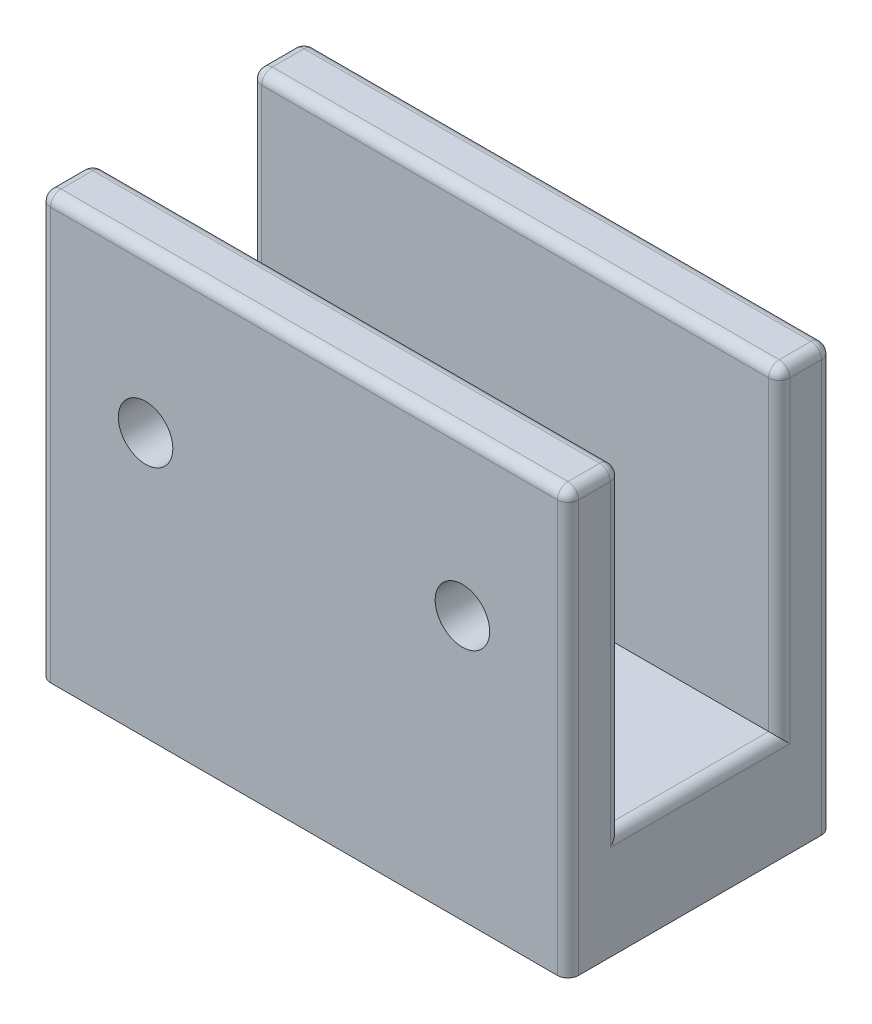
SolidWorks part; units mm, degrees
ref_plane "Front Plane" through (0, 0, 0) normal (0, 0, 1) x (1, 0, 0)
ref_plane "Top Plane" through (0, 0, 0) normal (0, 1, 0) x (1, 0, 0)
ref_plane "Right Plane" through (0, 0, 0) normal (1, 0, 0) x (0, 0, -1)
sketch "Sketch1" plane through (0, 0, 0) normal (0, 1, 0) x (1, 0, 0)
  line L1 (-25, -12.5) -> (25, -12.5)
  line L2 (-25, -12.5) -> (-25, 12.5)
  line L3 (-25, 12.5) -> (25, 12.5)
  line L4 (25, -12.5) -> (25, 12.5)
  line L5 (-25, -12.5) -> (25, 12.5) construction
  line L6 (-25, 12.5) -> (25, -12.5) construction
  point P0 (0, 0)
extrude "Boss-Extrude1" add sketch "Sketch1" along normal blind 40
sketch "Sketch2" plane through (0, 40, 0) normal (0, 1, 0) x (1, 0, 0)
  line L0 (25, -12.5) -> (25, 12.5) construction
  line L1 (-25, -7.5) -> (25, -7.5)
  line L2 (-25, -7.5) -> (-25, 7.5)
  line L3 (-25, 7.5) -> (25, 7.5)
  line L4 (25, -7.5) -> (25, 7.5)
  line L5 (-25, -7.5) -> (25, 7.5) construction
  line L6 (-25, 7.5) -> (25, -7.5) construction
  point P0 (0, 0)
extrude "Cut-Extrude1" cut sketch "Sketch2" against normal blind 30
fillet "Fillet1" radius 1 18 edges at (-25, 10, 0) (-25, 40, 10) (-25, 20, -12.5) (-25, 40, -10) (-25, 25, -7.5) (-25, 25, 7.5) (-25, 20, 12.5) (0, 40, 12.5) (0, 40, 7.5) (25, 40, -10) (25, 40, 10) (25, 20, 12.5) (25, 10, 0) (25, 25, 7.5) (0, 40, -12.5) (0, 40, -7.5) (25, 20, -12.5) (25, 25, -7.5)
sketch "Sketch3" plane through (0, 0, 12.5) normal (0, 0, 1) x (1, 0, 0)
  circle A0 centre (-15, 25) radius 2.5797
  circle A1 centre (15, 25) radius 2.5797
extrude "Cut-Extrude2" cut sketch "Sketch3" against normal up to next
sketch "Sketch4" plane through (0, 0, 0) normal (0, -1, 0) x (-1, 0, 0)
  circle A0 centre (0, 0) radius 2.5797
extrude "Cut-Extrude3" cut sketch "Sketch4" against normal blind 8
